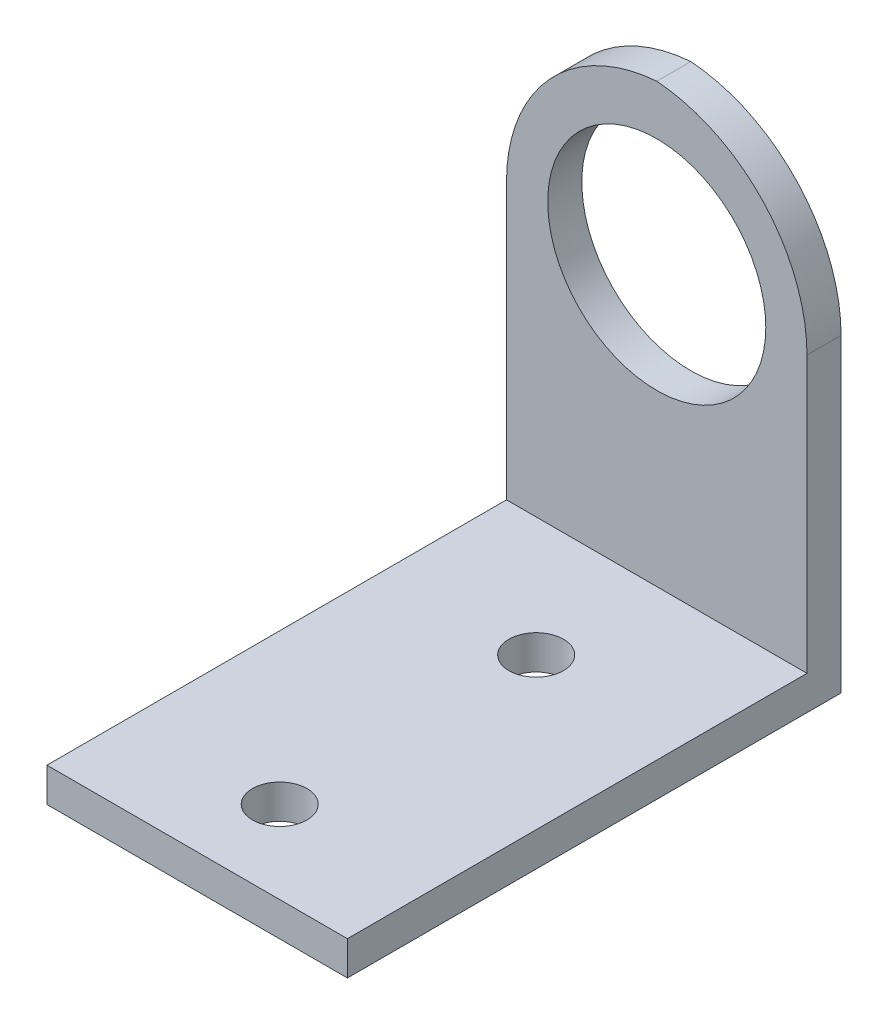
SolidWorks part; units mm, degrees
material "Fundición maleable"
ref_plane "Alzado" through (0, 0, 0) normal (0, 0, 1) x (1, 0, 0)
ref_plane "Planta" through (0, 0, 0) normal (0, 1, 0) x (1, 0, 0)
ref_plane "Vista lateral" through (0, 0, 0) normal (1, 0, 0) x (0, 0, -1)
sketch "Croquis1" plane through (0, 0, 0) normal (0, 0, 1) x (1, 0, 0)
  line L0 (-38.1, 0) -> (38.1, 0)
  line L1 (35, -110) -> (-35, -110)
  line L2 (35, -110) -> (35, 72.154)
  line L3 (-2.846, 110) -> (2.846, 110)
  line L4 (-35, -110) -> (-35, 72.154)
  line L5 (35, -110) -> (-35, 110) construction
  line L6 (35, 110) -> (-35, -110) construction
  circle A0 centre (0, 72.9) radius 25.4
  arc A1 (35, 72.154) -> (-2.846, 110) centre (-2.846, 72.154) ccw
  arc A2 (2.846, 110) -> (-35, 72.154) centre (2.846, 72.154) ccw
  point P2 (0, 0)
  point P16 (0, 0)
  dimension "D2" = 50.8
  dimension "D1" = 72.9
  dimension "D3" = 70
extrude "Saliente-Extruir1" add sketch "Croquis1" along normal blind 7.9375 contours L4 L0 L2 L3 A0
sketch "Croquis2" plane through (0, 0, 0) normal (0, -1, 0) x (1, 0, 0)
  line L1 (-35, 0) -> (35, 0)
  line L2 (-35, 0) -> (-35, 115)
  line L3 (-35, 115) -> (35, 115)
  line L4 (35, 0) -> (35, 115)
  circle A0 centre (-0.254, 35.7726) radius 6.35
  circle A1 centre (0, 95.7726) radius 6.35
  dimension "D1" = 12.7
  dimension "D2" = 12.7
  dimension "D3" = 60
  dimension "D4" = 115
  dimension "D5" = 70
extrude "Saliente-Extruir2" add sketch "Croquis2" against normal blind 7.9375
